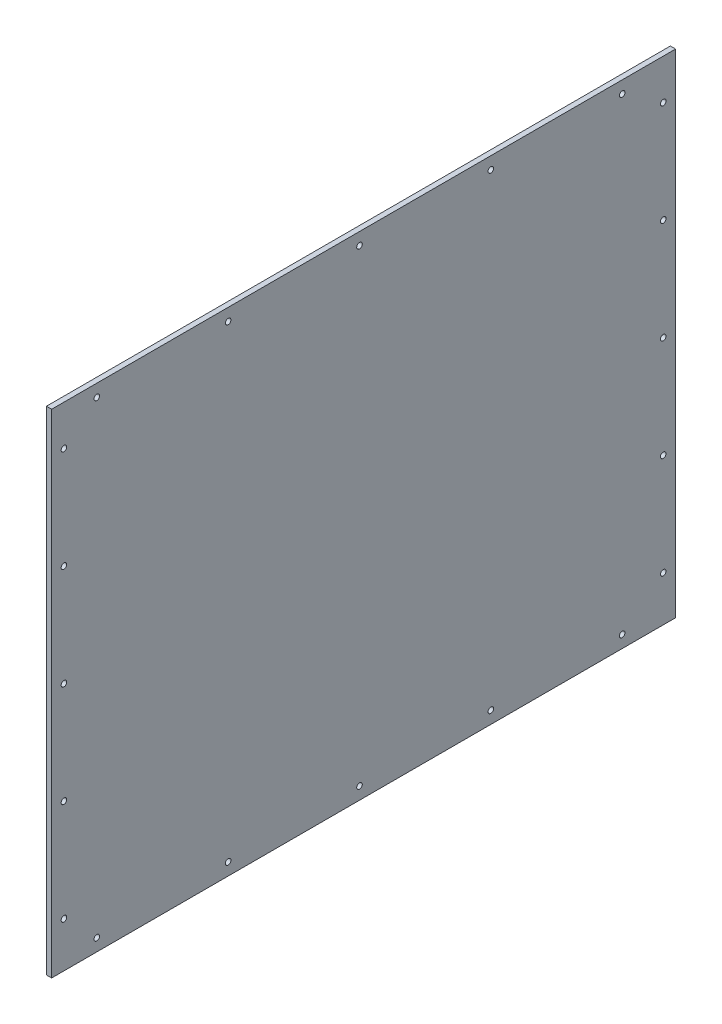
SolidWorks part; units mm, degrees
material "Acrylic (Medium-high impact)"
ref_plane "Front Plane" through (0, 0, 0) normal (0, 0, 1) x (1, 0, 0)
ref_plane "Top Plane" through (0, 0, 0) normal (0, 1, 0) x (1, 0, 0)
ref_plane "Right Plane" through (0, 0, 0) normal (1, 0, 0) x (0, 0, -1)
sketch "Sketch1" plane through (244.6938, 0, 0) normal (1, 0, 0) x (0, 0, -1)
  line L1 (-423.6991, 163.36) -> (-43.6991, 163.36)
  line L2 (-423.6991, 163.36) -> (-423.6991, -136.64)
  line L3 (-423.6991, -136.64) -> (-43.6991, -136.64)
  line L4 (-43.6991, 163.36) -> (-43.6991, -136.64)
extrude "Plate" add sketch "Sketch1" along normal blind 3.175
sketch "Sketch2" plane through (247.8688, 0, 0) normal (1, 0, 0) x (0, 0, -1)
  line L12 (-416.1991, -129.14) -> (-51.1991, -129.14)
  line L13 (-51.1991, -129.14) -> (-51.1991, 155.86)
  line L14 (-51.1991, 155.86) -> (-416.1991, 155.86)
  line L15 (-416.1991, 155.86) -> (-416.1991, -129.14)
  line L16 (-416.1991, -129.14) -> (-51.1991, -129.14) construction
  line L17 (-51.1991, -129.14) -> (-51.1991, 155.86) construction
  line L18 (-51.1991, 155.86) -> (-416.1991, 155.86) construction
  line L19 (-416.1991, 155.86) -> (-416.1991, -129.14) construction
  circle A0 centre (-396.1991, 155.86) radius 1.7
  circle A1 centre (-396.1991, -129.14) radius 1.7
  circle A2 centre (-316.1991, 155.86) radius 1.7
  circle A3 centre (-316.1991, -129.14) radius 1.7
  circle A4 centre (-236.1991, 155.86) radius 1.7
  circle A5 centre (-236.1991, -129.14) radius 1.7
  circle A6 centre (-156.1991, 155.86) radius 1.7
  circle A7 centre (-156.1991, -129.14) radius 1.7
  circle A8 centre (-76.1991, 155.86) radius 1.7
  circle A9 centre (-76.1991, -129.14) radius 1.7
  circle A10 centre (-416.1991, -109.14) radius 1.7
  circle A11 centre (-51.1991, -109.14) radius 1.7
  circle A12 centre (-51.1991, -47.14) radius 1.7
  circle A13 centre (-416.1991, -47.14) radius 1.7
  circle A14 centre (-51.1991, 14.86) radius 1.7
  circle A15 centre (-416.1991, 14.86) radius 1.7
  circle A16 centre (-51.1991, 76.86) radius 1.7
  circle A17 centre (-416.1991, 76.86) radius 1.7
  circle A18 centre (-51.1991, 138.86) radius 1.7
  circle A19 centre (-416.1991, 138.86) radius 1.7
  dimension "D2" = 3.4
  dimension "D3" = 20
  dimension "D4" = 20
  dimension "D6" = 20
  dimension "D7" = 20
  dimension "D1" = 7.5
  dimension "D5" = 5
  dimension "D8" = 5
extrude "Rail_Mounts" cut sketch "Sketch2" against normal up to next
